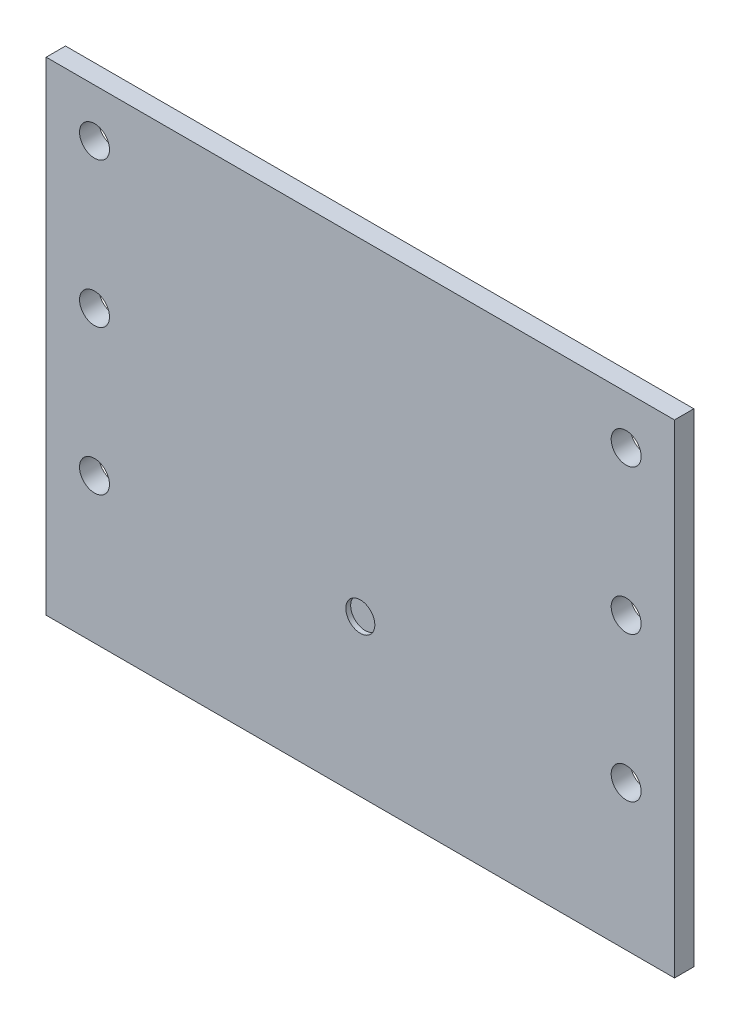
SolidWorks part; units mm, degrees
ref_plane "前视基准面" through (0, 0, 0) normal (0, 0, 1) x (1, 0, 0)
ref_plane "上视基准面" through (0, 0, 0) normal (0, 1, 0) x (1, 0, 0)
ref_plane "右视基准面" through (0, 0, 0) normal (1, 0, 0) x (0, 0, -1)
sketch "草图2" plane through (0, 0, 0) normal (0, 0, 1) x (1, 0, 0)
  line L1 (-105, 50) -> (105, 50)
  line L2 (-105, 50) -> (-105, -50)
  line L3 (-105, -50) -> (105, -50)
  line L4 (105, 50) -> (105, -50)
  line L5 (-105, 50) -> (105, -50) construction
  line L6 (-105, -50) -> (105, 50) construction
  point P0 (0, 0)
  dimension "D1" = 100
  dimension "D2" = 210
extrude "凸台-拉伸1" add sketch "草图2" along normal blind 4
sketch "草图7" plane through (0, 0, 4) normal (0, 0, 1) x (1, 0, 0)
  circle A2 centre (0, -17.7376) radius 3
  dimension "D1" = 6
extrude "切除-拉伸2" cut sketch "草图7" against normal blind 1
sketch "草图8" plane through (0, 0, 4) normal (0, 0, 1) x (1, 0, 0)
  line L0 (0, 31.5744) -> (0, 0) construction
  line L1 (-60, 50) -> (60, 50)
  line L2 (-60, 50) -> (-60, -50)
  line L3 (-60, -50) -> (60, -50)
  line L4 (60, 50) -> (60, -50)
  line L5 (-60, 50) -> (60, -50) construction
  line L6 (-60, -50) -> (60, 50) construction
  line L7 (-50, 50) -> (-50, -50) construction
  line L8 (105, 50) -> (-105, 50) construction
  circle A0 centre (-55, 40) radius 3.1
  circle A1 centre (-55, -20) radius 3.1
  circle A2 centre (-55, 10) radius 3.1
  circle A3 centre (55, 40) radius 3.1
  circle A4 centre (55, 10) radius 3.1
  circle A5 centre (55, -20) radius 3.1
  point P0 (0, 0)
  point P16 (-55, -20.5685)
  point P17 (-55, 15.5559)
  point P20 (-56.4947, -20.3547)
  point P25 (0, 0)
  point P26 (0, 0)
  dimension "D4" = 6.2
  dimension "D6" = 6.2
  dimension "D7" = 6.2
  dimension "D1" = 100
  dimension "D2" = 120
  dimension "D3" = 50
  dimension "D5" = 5
  dimension "D8" = 60
  dimension "D9" = 30
  dimension "D10" = 10
extrude "切除-拉伸3" cut sketch "草图8" against normal blind 60 contours A2 | A0 | A1 | A3 | A4 | A5
sketch "草图11" plane through (0, 0, 0) normal (0, 0, -1) x (-1, 0, 0)
  line L0 (105, -50) -> (-105, -50) construction
  line L1 (-65, 50) -> (65, 50)
  line L2 (-65, 50) -> (-65, -50)
  line L3 (-65, -50) -> (65, -50)
  line L4 (65, 50) -> (65, -50)
  line L5 (-65, 50) -> (65, -50) construction
  line L6 (-65, -50) -> (65, 50) construction
  circle A0 centre (55, 40) radius 3.1
  point P0 (0, 0)
  dimension "D1" = 10
extrude "切除-拉伸5" cut sketch "草图11" against normal blind 100 flip side to cut
